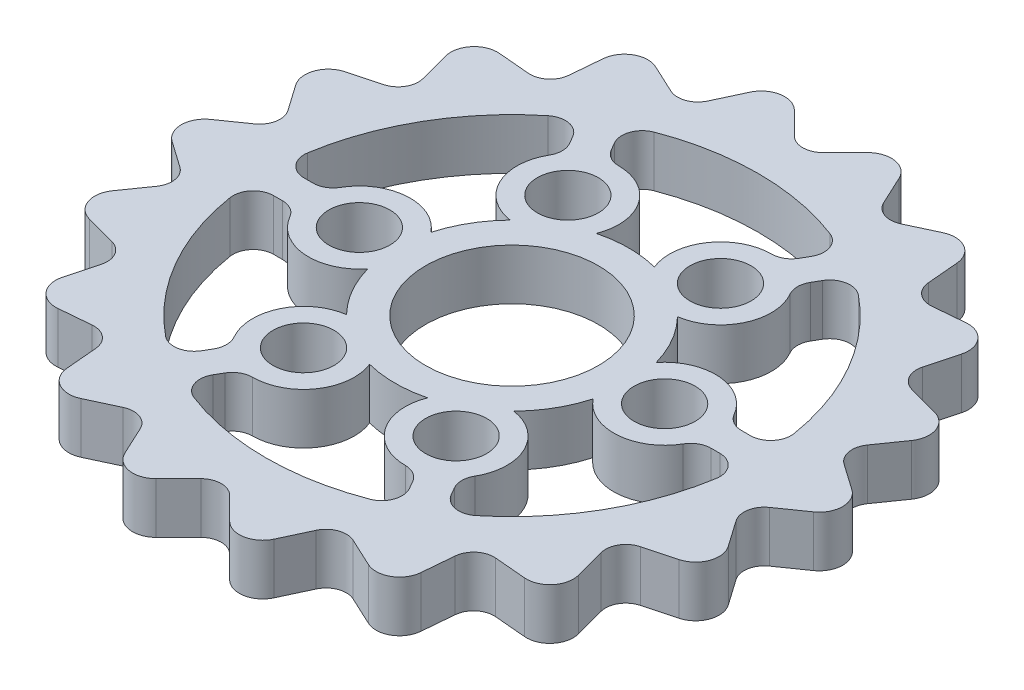
SolidWorks part; units mm, degrees
ref_plane "Front Plane" through (0, 0, 0) normal (0, 0, 1) x (1, 0, 0)
ref_plane "Top Plane" through (0, 0, 0) normal (0, 1, 0) x (1, 0, 0)
ref_plane "Right Plane" through (0, 0, 0) normal (1, 0, 0) x (0, 0, -1)
sketch "Sketch1" plane through (0, 0, 0) normal (0, 1, 0) x (1, 0, 0)
  line L0 (0, 0) -> (41.275, 0) construction
  line L1 (38.354, 0) -> (40.0294, 2.3927) construction
  line L2 (38.354, 0) -> (40.0294, -2.3927) construction
  line L3 (40.0294, -2.3927) -> (29.0286, -10.0956)
  line L4 (40.0294, 2.3927) -> (29.0286, 10.0956)
  circle A0 centre (0, 0) radius 41.275 construction
  arc A1 (40.0294, 2.3927) -> (40.0294, -2.3927) centre (38.354, 0) cw
  arc A2 (29.0286, 10.0956) -> (29.0286, -10.0956) centre (0, 0) cw
  point P9 (30.734, 0)
  dimension "D1" = 82.55
  dimension "D2" = 2.921
  dimension "D5" = 7.62
  dimension "D3" = 55
  dimension "D4" = 55
extrude "Boss-Extrude1" add sketch "Sketch1" along normal mid plane 6.35
pattern_circular "CirPattern1" count 18 over 360 about axis through (0, 0, 0) along (0, 1, 0) of "Boss-Extrude1"
fillet "Fillet1" radius 2.54 18 edges at (30.5206, 0, -17.6211) (22.6532, 0, -26.997) (12.0535, 0, -33.1168) (0, 0, -35.2421) (-12.0535, 0, -33.1168) (-22.6532, 0, -26.997) (-30.5206, 0, -17.6211) (-34.7067, 0, -6.1197) (-34.7067, 0, 6.1197) (-30.5206, 0, 17.6211) (-22.6532, 0, 26.997) (-12.0535, 0, 33.1168) (0, 0, 35.2421) (12.0535, 0, 33.1168) (22.6532, 0, 26.997) (30.5206, 0, 17.6211) (34.7067, 0, 6.1197) (34.7067, 0, -6.1197)
sketch "Sketch2" plane through (0, 3.175, 0) normal (0, 1, 0) x (1, 0, 0)
  line L2 (0, 0) -> (14.0652, 0) construction
  line L3 (14.0652, 3.9338) -> (14.0652, -3.9338) construction
  line L4 (14.0652, 0) -> (19.05, 0) construction
  line L7 (30.6749, 1.905) -> (25.1075, 1.905)
  line L8 (30.6749, -1.905) -> (25.1075, -1.905)
  circle A0 centre (0, 0) radius 10.795
  circle A1 centre (0, 0) radius 14.605 construction
  circle A2 centre (0, 0) radius 30.734 construction
  arc A3 (14.0652, 3.9338) -> (14.0652, -3.9338) centre (0, 0) ccw
  arc A4 (30.6749, 1.905) -> (30.6749, -1.905) centre (0, 0) cw
  circle A6 centre (19.05, 0) radius 6.35 construction
  circle A7 centre (19.05, 0) radius 3.81
  arc A8 (14.0652, 3.9338) -> (25.1075, 1.905) centre (19.05, 0) cw
  arc A9 (14.0652, -3.9338) -> (25.1075, -1.905) centre (19.05, 0) ccw
  point P11 (14.0652, 0)
  dimension "D1" = 21.59
  dimension "D2" = 29.21
  dimension "D4" = 7.62
  dimension "D5" = 12.7
  dimension "D6" = 19.05
extrude "Boss-Extrude2" add sketch "Sketch2" against normal blind 6.35
fillet "Fillet3" radius 2.54 4 edges at (30.6749, 0, 1.905) (30.6749, 0, -1.905) (25.1075, 0, 1.905) (25.1075, 0, -1.905)
pattern_circular "CirPattern6" count 6 over 360 about axis through (0, 0, 0) along (0, 1, 0) of "Boss-Extrude2", "Fillet3"
